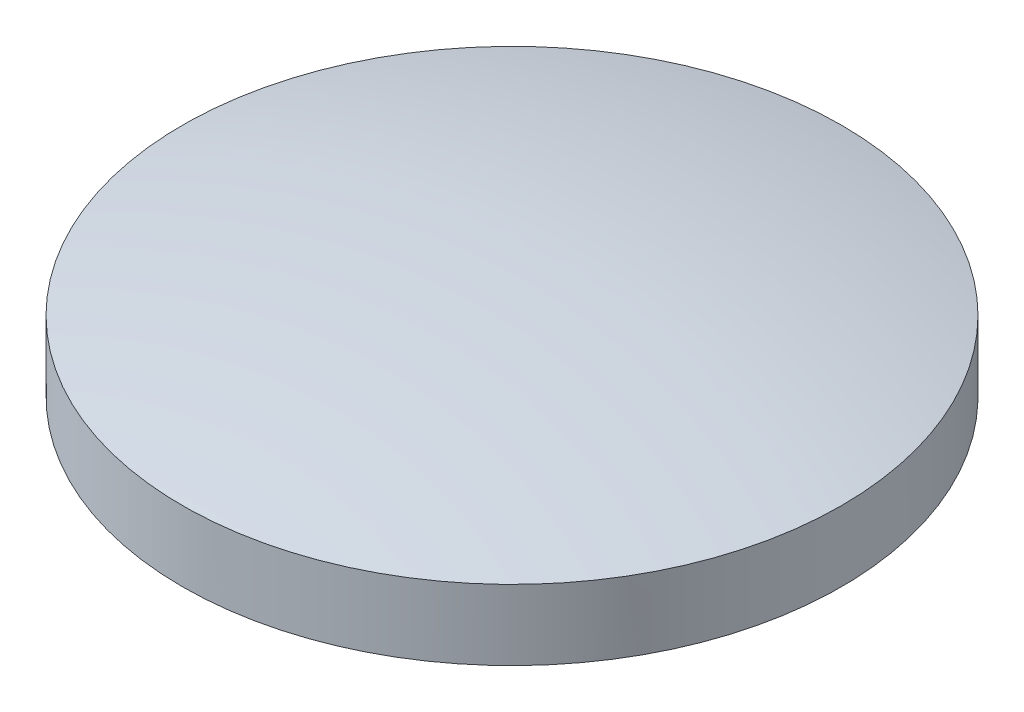
SolidWorks part; units mm, degrees
material "PVC Rígido"
ref_plane "Alzado" through (0, 0, 0) normal (0, 0, 1) x (1, 0, 0)
ref_plane "Planta" through (0, 0, 0) normal (0, 1, 0) x (1, 0, 0)
ref_plane "Vista lateral" through (0, 0, 0) normal (1, 0, 0) x (0, 0, -1)
sketch "Croquis1" plane through (0, 0, 0) normal (0, 0, 1) x (1, 0, 0)
  line L0 (0, 0) -> (0, 20.2053) construction
  line L1 (0, 0) -> (57, 0) construction
  line L2 (57, 0) -> (59.5, 0)
  line L3 (59.5, 0) -> (59.5, 12.7)
  line L4 (0, 20.2053) -> (0, 17.7053)
  line L7 (57, 0) -> (57, 10.7519)
  arc A0 (0, 20.2053) -> (59.5, 12.7) centre (0, -219.3973) cw
  arc A1 (0, 17.7053) -> (57, 10.7519) centre (0, -219.3973) cw
  dimension "D1" = 12.7
  dimension "D3" = 57
  dimension "D4" = 2.5
revolve "Revolución1" add sketch "Croquis1" angle 360 about L0
